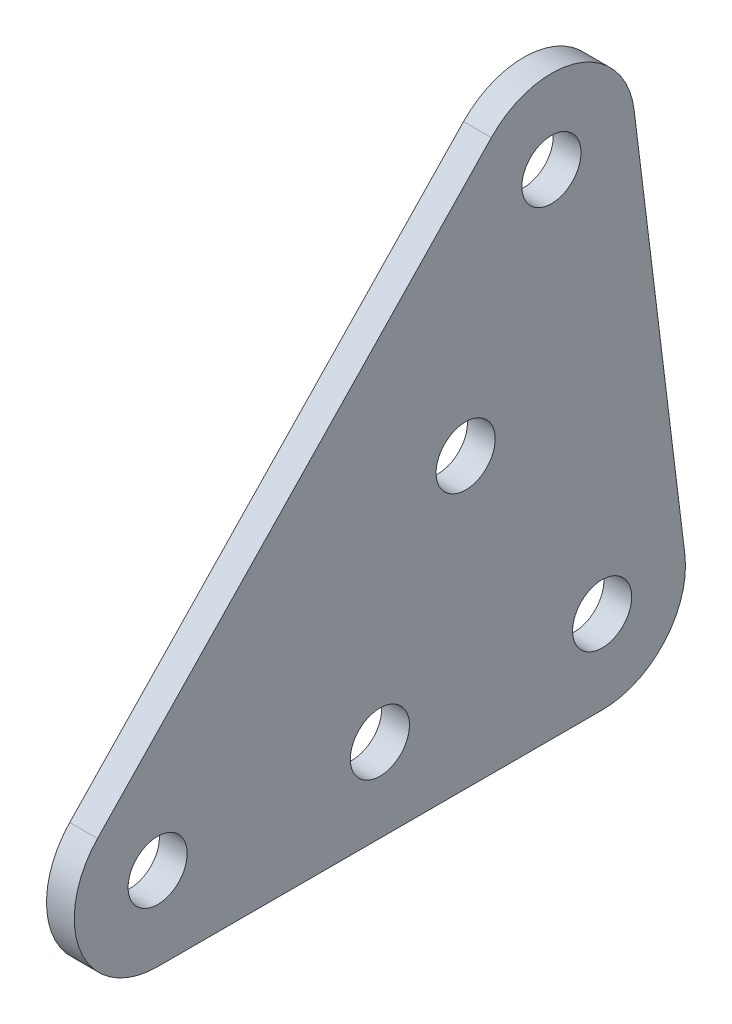
SolidWorks part; units mm, degrees
ref_plane "Front Plane" through (0, 0, 0) normal (0, 0, 1) x (1, 0, 0)
ref_plane "Top Plane" through (0, 0, 0) normal (0, 1, 0) x (1, 0, 0)
ref_plane "Right Plane" through (0, 0, 0) normal (1, 0, 0) x (0, 0, -1)
sketch "Sketch1" plane through (0, 0, 0) normal (1, 0, 0) x (0, 0, -1)
  line L0 (-1172.1145, 198.3666) -> (-1217.1195, 151.5021) construction
  line L1 (-1210.2494, 135.3796) -> (-1159.4494, 135.3796) construction
  line L3 (-1155.7914, 192.938) -> (-1149.9964, 146.0735) construction
  line L5 (-1155.7914, 192.938) -> (-1149.9964, 146.0735)
  line L8 (-1172.1145, 198.3666) -> (-1217.1195, 151.5021)
  line L9 (-1210.2494, 135.3796) -> (-1159.4494, 135.3796)
  circle A0 centre (-1159.4494, 144.9046) radius 9.525 construction
  circle A1 centre (-1210.2494, 144.9046) radius 9.525 construction
  circle A3 centre (-1165.2444, 191.7691) radius 9.525 construction
  arc A4 (-1159.4494, 135.3796) -> (-1149.9964, 146.0735) centre (-1159.4494, 144.9046) ccw
  arc A6 (-1217.1195, 151.5021) -> (-1210.2494, 135.3796) centre (-1210.2494, 144.9046) ccw
  arc A10 (-1155.7914, 192.938) -> (-1172.1145, 198.3666) centre (-1165.2444, 191.7691) ccw
extrude "Boss-Extrude1" add sketch "Sketch1" against normal up to vertex from vertex
hole_wizard "1/4 Clearance Hole1" positions "Sketch2" profile "Sketch3" hole size "1/4" standard "ANSI Inch" end condition through all
sketch "Sketch2" plane through (96.0438, 0, 0) normal (1, 0, 0) x (0, 0, -1)
  point P2 (-1175.0469, 168.3368)
  point P5 (-1165.2444, 191.7691)
  point P17 (-1210.2494, 144.9046)
  point P20 (-1184.8494, 144.9046)
  point P22 (-1159.4494, 144.9046)
sketch "Sketch3" plane through (96.0438, 168.3368, 1175.0469) normal (0, 1, 0) x (0, 0, -1)
  line L0 (0, 0) -> (0, 3.175)
  line L1 (0, 3.175) -> (3.3782, 3.175)
  line L2 (3.3782, 3.175) -> (3.3782, 0)
  line L5 (3.3782, 0) -> (0, 0)
  line L11 (0, -6.35) -> (0, 107.95) construction
  dimension "Thru Hole Dia." = 6.7564
  dimension "Thru Hole Depth" = 3.175
